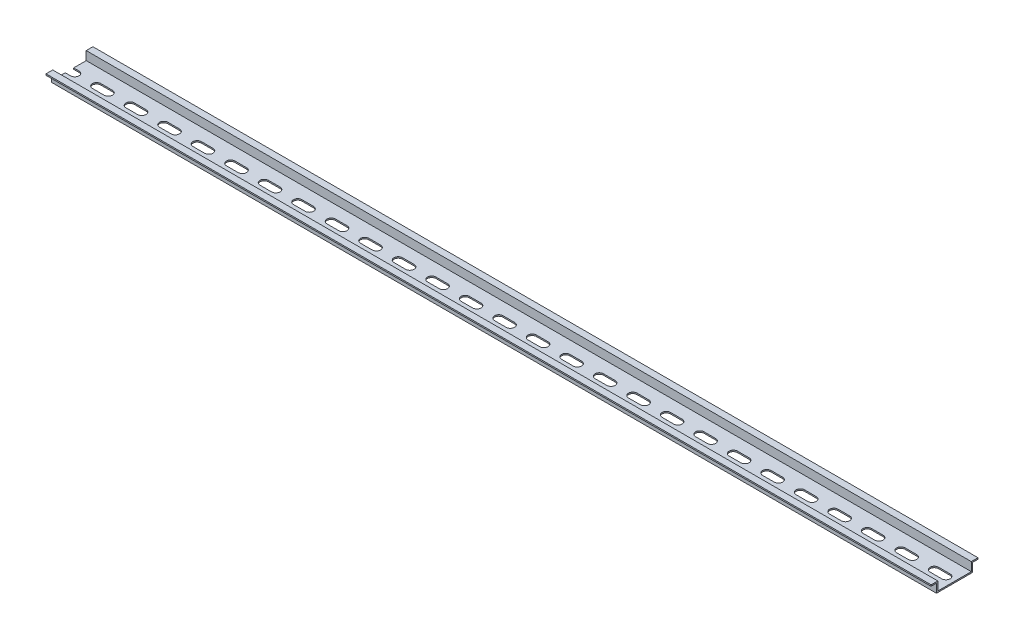
SolidWorks part; units mm, degrees
material "Plain Carbon Steel"
ref_plane "Front Plane" through (0, 0, 0) normal (0, 0, 1) x (1, 0, 0)
ref_plane "Top Plane" through (0, 0, 0) normal (0, 1, 0) x (1, 0, 0)
ref_plane "Right Plane" through (0, 0, 0) normal (1, 0, 0) x (0, 0, -1)
sketch "Sketch1" plane through (0, 0, 0) normal (0, 0, 1) x (1, 0, 0)
  line L1 (-500, 0) -> (500, 0)
  line L2 (-500, 0) -> (-500, 7.5)
  line L3 (-500, 7.5) -> (500, 7.5)
  line L4 (500, 0) -> (500, 7.5)
  point P0 (0, 0)
  point P7 (0, 0)
  dimension "D1" = 1000
  dimension "D2" = 7.5
extrude "Boss-Extrude1" add sketch "Sketch1" along normal mid plane 35
sketch "Sketch2" plane through (0, 7.5, 0) normal (0, 1, 0) x (1, 0, 0)
  line L0 (-500, -17.5) -> (-500, 17.5) construction
  line L1 (-500, -12.5) -> (500, -12.5)
  line L2 (-500, -12.5) -> (-500, 12.5)
  line L3 (-500, 12.5) -> (500, 12.5)
  line L4 (500, -12.5) -> (500, 12.5)
  line L5 (500, -17.5) -> (500, 17.5) construction
  line L6 (-500, 0) -> (500, 0) construction
  point P10 (0, 0)
  dimension "D1" = 25
extrude "Cut-Extrude1" cut sketch "Sketch2" against normal offset from surface (6.5 mm away) 1 up to face at (0, 0, 0)
sketch "Sketch4" plane through (500, 0, 0) normal (1, 0, 0) x (0, 0, -1)
  line L0 (0, 0) -> (0, 6.5) construction
  line L1 (-17.5, 0) -> (-13.5, 0)
  line L2 (-17.5, 0) -> (-17.5, 6.5)
  line L4 (-13.5, 0) -> (-13.5, 6.5)
  line L5 (17.5, 0) -> (13.5, 0)
  line L6 (17.5, 0) -> (17.5, 6.5)
  line L7 (17.5, 6.5) -> (13.5, 6.5)
  line L8 (13.5, 0) -> (13.5, 6.5)
  line L9 (-17.5, 0) -> (17.5, 0) construction
  line L11 (-17.5, 6.5) -> (-13.5, 6.5)
  line L12 (-17.5, 7.5) -> (-12.5, 7.5) construction
  line L13 (-12.5, 1) -> (-12.5, 7.5) construction
  dimension "D1" = 1
  dimension "D2" = 1
extrude "Cut-Extrude2" cut sketch "Sketch4" against normal through all both and the other way through all
sketch "Sketch5" plane through (0, 1, 0) normal (0, 1, 0) x (1, 0, 0)
  line L0 (-504.69, 0) -> (-496.01, 0) construction
  line L1 (-504.69, 3.16) -> (-496.01, 3.16)
  line L2 (-504.69, -3.16) -> (-496.01, -3.16)
  line L3 (-500, -12.5) -> (-500, 12.5) construction
  line L4 (-504.69, 0) -> (-479.69, 0) construction
  line L5 (-492.85, 0) -> (-482.85, 0) construction
  line L6 (-479.69, 0) -> (-471.01, 0) construction
  line L7 (-479.69, 3.16) -> (-471.01, 3.16)
  line L8 (-479.69, -3.16) -> (-471.01, -3.16)
  line L9 (-454.69, 0) -> (-446.01, 0) construction
  line L10 (-454.69, 3.16) -> (-446.01, 3.16)
  line L11 (-454.69, -3.16) -> (-446.01, -3.16)
  line L12 (-429.69, 0) -> (-421.01, 0) construction
  line L13 (-429.69, 3.16) -> (-421.01, 3.16)
  line L14 (-429.69, -3.16) -> (-421.01, -3.16)
  line L15 (-404.69, 0) -> (-396.01, 0) construction
  line L16 (-404.69, 3.16) -> (-396.01, 3.16)
  line L17 (-404.69, -3.16) -> (-396.01, -3.16)
  line L18 (-379.69, 0) -> (-371.01, 0) construction
  line L19 (-379.69, 3.16) -> (-371.01, 3.16)
  line L20 (-379.69, -3.16) -> (-371.01, -3.16)
  line L21 (-354.69, 0) -> (-346.01, 0) construction
  line L22 (-354.69, 3.16) -> (-346.01, 3.16)
  line L23 (-354.69, -3.16) -> (-346.01, -3.16)
  line L24 (-329.69, 0) -> (-321.01, 0) construction
  line L25 (-329.69, 3.16) -> (-321.01, 3.16)
  line L26 (-329.69, -3.16) -> (-321.01, -3.16)
  line L27 (-304.69, 0) -> (-296.01, 0) construction
  line L28 (-304.69, 3.16) -> (-296.01, 3.16)
  line L29 (-304.69, -3.16) -> (-296.01, -3.16)
  line L30 (-279.69, 0) -> (-271.01, 0) construction
  line L31 (-279.69, 3.16) -> (-271.01, 3.16)
  line L32 (-279.69, -3.16) -> (-271.01, -3.16)
  line L33 (-254.69, 0) -> (-246.01, 0) construction
  line L34 (-254.69, 3.16) -> (-246.01, 3.16)
  line L35 (-254.69, -3.16) -> (-246.01, -3.16)
  line L36 (-229.69, 0) -> (-221.01, 0) construction
  line L37 (-229.69, 3.16) -> (-221.01, 3.16)
  line L38 (-229.69, -3.16) -> (-221.01, -3.16)
  line L39 (-204.69, 0) -> (-196.01, 0) construction
  line L40 (-204.69, 3.16) -> (-196.01, 3.16)
  line L41 (-204.69, -3.16) -> (-196.01, -3.16)
  line L42 (-179.69, 0) -> (-171.01, 0) construction
  line L43 (-179.69, 3.16) -> (-171.01, 3.16)
  line L44 (-179.69, -3.16) -> (-171.01, -3.16)
  line L45 (-154.69, 0) -> (-146.01, 0) construction
  line L46 (-154.69, 3.16) -> (-146.01, 3.16)
  line L47 (-154.69, -3.16) -> (-146.01, -3.16)
  line L48 (-129.69, 0) -> (-121.01, 0) construction
  line L49 (-129.69, 3.16) -> (-121.01, 3.16)
  line L50 (-129.69, -3.16) -> (-121.01, -3.16)
  line L51 (-104.69, 0) -> (-96.01, 0) construction
  line L52 (-104.69, 3.16) -> (-96.01, 3.16)
  line L53 (-104.69, -3.16) -> (-96.01, -3.16)
  line L54 (-79.69, 0) -> (-71.01, 0) construction
  line L55 (-79.69, 3.16) -> (-71.01, 3.16)
  line L56 (-79.69, -3.16) -> (-71.01, -3.16)
  line L57 (-54.69, 0) -> (-46.01, 0) construction
  line L58 (-54.69, 3.16) -> (-46.01, 3.16)
  line L59 (-54.69, -3.16) -> (-46.01, -3.16)
  line L60 (-29.69, 0) -> (-21.01, 0) construction
  line L61 (-29.69, 3.16) -> (-21.01, 3.16)
  line L62 (-29.69, -3.16) -> (-21.01, -3.16)
  line L63 (-4.69, 0) -> (3.99, 0) construction
  line L64 (-4.69, 3.16) -> (3.99, 3.16)
  line L65 (-4.69, -3.16) -> (3.99, -3.16)
  line L66 (20.31, 0) -> (28.99, 0) construction
  line L67 (20.31, 3.16) -> (28.99, 3.16)
  line L68 (20.31, -3.16) -> (28.99, -3.16)
  line L69 (45.31, 0) -> (53.99, 0) construction
  line L70 (45.31, 3.16) -> (53.99, 3.16)
  line L71 (45.31, -3.16) -> (53.99, -3.16)
  line L72 (70.31, 0) -> (78.99, 0) construction
  line L73 (70.31, 3.16) -> (78.99, 3.16)
  line L74 (70.31, -3.16) -> (78.99, -3.16)
  line L75 (95.31, 0) -> (103.99, 0) construction
  line L76 (95.31, 3.16) -> (103.99, 3.16)
  line L77 (95.31, -3.16) -> (103.99, -3.16)
  line L78 (120.31, 0) -> (128.99, 0) construction
  line L79 (120.31, 3.16) -> (128.99, 3.16)
  line L80 (120.31, -3.16) -> (128.99, -3.16)
  line L81 (145.31, 0) -> (153.99, 0) construction
  line L82 (145.31, 3.16) -> (153.99, 3.16)
  line L83 (145.31, -3.16) -> (153.99, -3.16)
  line L84 (170.31, 0) -> (178.99, 0) construction
  line L85 (170.31, 3.16) -> (178.99, 3.16)
  line L86 (170.31, -3.16) -> (178.99, -3.16)
  line L87 (195.31, 0) -> (203.99, 0) construction
  line L88 (195.31, 3.16) -> (203.99, 3.16)
  line L89 (195.31, -3.16) -> (203.99, -3.16)
  line L90 (220.31, 0) -> (228.99, 0) construction
  line L91 (220.31, 3.16) -> (228.99, 3.16)
  line L92 (220.31, -3.16) -> (228.99, -3.16)
  line L93 (245.31, 0) -> (253.99, 0) construction
  line L94 (245.31, 3.16) -> (253.99, 3.16)
  line L95 (245.31, -3.16) -> (253.99, -3.16)
  line L96 (270.31, 0) -> (278.99, 0) construction
  line L97 (270.31, 3.16) -> (278.99, 3.16)
  line L98 (270.31, -3.16) -> (278.99, -3.16)
  line L99 (295.31, 0) -> (303.99, 0) construction
  line L100 (295.31, 3.16) -> (303.99, 3.16)
  line L101 (295.31, -3.16) -> (303.99, -3.16)
  line L102 (320.31, 0) -> (328.99, 0) construction
  line L103 (320.31, 3.16) -> (328.99, 3.16)
  line L104 (320.31, -3.16) -> (328.99, -3.16)
  line L105 (345.31, 0) -> (353.99, 0) construction
  line L106 (345.31, 3.16) -> (353.99, 3.16)
  line L107 (345.31, -3.16) -> (353.99, -3.16)
  line L108 (370.31, 0) -> (378.99, 0) construction
  line L109 (370.31, 3.16) -> (378.99, 3.16)
  line L110 (370.31, -3.16) -> (378.99, -3.16)
  line L111 (395.31, 0) -> (403.99, 0) construction
  line L112 (395.31, 3.16) -> (403.99, 3.16)
  line L113 (395.31, -3.16) -> (403.99, -3.16)
  line L114 (420.31, 0) -> (428.99, 0) construction
  line L115 (420.31, 3.16) -> (428.99, 3.16)
  line L116 (420.31, -3.16) -> (428.99, -3.16)
  line L117 (445.31, 0) -> (453.99, 0) construction
  line L118 (445.31, 3.16) -> (453.99, 3.16)
  line L119 (445.31, -3.16) -> (453.99, -3.16)
  line L120 (470.31, 0) -> (478.99, 0) construction
  line L121 (470.31, 3.16) -> (478.99, 3.16)
  line L122 (470.31, -3.16) -> (478.99, -3.16)
  line L123 (495.31, 0) -> (503.99, 0) construction
  line L124 (495.31, 3.16) -> (503.99, 3.16)
  line L125 (495.31, -3.16) -> (503.99, -3.16)
  arc A0 (-504.69, 3.16) -> (-504.69, -3.16) centre (-504.69, 0) ccw
  arc A1 (-496.01, -3.16) -> (-496.01, 3.16) centre (-496.01, 0) ccw
  arc A2 (-479.69, 3.16) -> (-479.69, -3.16) centre (-479.69, 0) ccw
  arc A3 (-471.01, -3.16) -> (-471.01, 3.16) centre (-471.01, 0) ccw
  arc A4 (-454.69, 3.16) -> (-454.69, -3.16) centre (-454.69, 0) ccw
  arc A5 (-446.01, -3.16) -> (-446.01, 3.16) centre (-446.01, 0) ccw
  arc A6 (-429.69, 3.16) -> (-429.69, -3.16) centre (-429.69, 0) ccw
  arc A7 (-421.01, -3.16) -> (-421.01, 3.16) centre (-421.01, 0) ccw
  arc A8 (-404.69, 3.16) -> (-404.69, -3.16) centre (-404.69, 0) ccw
  arc A9 (-396.01, -3.16) -> (-396.01, 3.16) centre (-396.01, 0) ccw
  arc A10 (-379.69, 3.16) -> (-379.69, -3.16) centre (-379.69, 0) ccw
  arc A11 (-371.01, -3.16) -> (-371.01, 3.16) centre (-371.01, 0) ccw
  arc A12 (-354.69, 3.16) -> (-354.69, -3.16) centre (-354.69, 0) ccw
  arc A13 (-346.01, -3.16) -> (-346.01, 3.16) centre (-346.01, 0) ccw
  arc A14 (-329.69, 3.16) -> (-329.69, -3.16) centre (-329.69, 0) ccw
  arc A15 (-321.01, -3.16) -> (-321.01, 3.16) centre (-321.01, 0) ccw
  arc A16 (-304.69, 3.16) -> (-304.69, -3.16) centre (-304.69, 0) ccw
  arc A17 (-296.01, -3.16) -> (-296.01, 3.16) centre (-296.01, 0) ccw
  arc A18 (-279.69, 3.16) -> (-279.69, -3.16) centre (-279.69, 0) ccw
  arc A19 (-271.01, -3.16) -> (-271.01, 3.16) centre (-271.01, 0) ccw
  arc A20 (-254.69, 3.16) -> (-254.69, -3.16) centre (-254.69, 0) ccw
  arc A21 (-246.01, -3.16) -> (-246.01, 3.16) centre (-246.01, 0) ccw
  arc A22 (-229.69, 3.16) -> (-229.69, -3.16) centre (-229.69, 0) ccw
  arc A23 (-221.01, -3.16) -> (-221.01, 3.16) centre (-221.01, 0) ccw
  arc A24 (-204.69, 3.16) -> (-204.69, -3.16) centre (-204.69, 0) ccw
  arc A25 (-196.01, -3.16) -> (-196.01, 3.16) centre (-196.01, 0) ccw
  arc A26 (-179.69, 3.16) -> (-179.69, -3.16) centre (-179.69, 0) ccw
  arc A27 (-171.01, -3.16) -> (-171.01, 3.16) centre (-171.01, 0) ccw
  arc A28 (-154.69, 3.16) -> (-154.69, -3.16) centre (-154.69, 0) ccw
  arc A29 (-146.01, -3.16) -> (-146.01, 3.16) centre (-146.01, 0) ccw
  arc A30 (-129.69, 3.16) -> (-129.69, -3.16) centre (-129.69, 0) ccw
  arc A31 (-121.01, -3.16) -> (-121.01, 3.16) centre (-121.01, 0) ccw
  arc A32 (-104.69, 3.16) -> (-104.69, -3.16) centre (-104.69, 0) ccw
  arc A33 (-96.01, -3.16) -> (-96.01, 3.16) centre (-96.01, 0) ccw
  arc A34 (-79.69, 3.16) -> (-79.69, -3.16) centre (-79.69, 0) ccw
  arc A35 (-71.01, -3.16) -> (-71.01, 3.16) centre (-71.01, 0) ccw
  arc A36 (-54.69, 3.16) -> (-54.69, -3.16) centre (-54.69, 0) ccw
  arc A37 (-46.01, -3.16) -> (-46.01, 3.16) centre (-46.01, 0) ccw
  arc A38 (-29.69, 3.16) -> (-29.69, -3.16) centre (-29.69, 0) ccw
  arc A39 (-21.01, -3.16) -> (-21.01, 3.16) centre (-21.01, 0) ccw
  arc A40 (-4.69, 3.16) -> (-4.69, -3.16) centre (-4.69, 0) ccw
  arc A41 (3.99, -3.16) -> (3.99, 3.16) centre (3.99, 0) ccw
  arc A42 (20.31, 3.16) -> (20.31, -3.16) centre (20.31, 0) ccw
  arc A43 (28.99, -3.16) -> (28.99, 3.16) centre (28.99, 0) ccw
  arc A44 (45.31, 3.16) -> (45.31, -3.16) centre (45.31, 0) ccw
  arc A45 (53.99, -3.16) -> (53.99, 3.16) centre (53.99, 0) ccw
  arc A46 (70.31, 3.16) -> (70.31, -3.16) centre (70.31, 0) ccw
  arc A47 (78.99, -3.16) -> (78.99, 3.16) centre (78.99, 0) ccw
  arc A48 (95.31, 3.16) -> (95.31, -3.16) centre (95.31, 0) ccw
  arc A49 (103.99, -3.16) -> (103.99, 3.16) centre (103.99, 0) ccw
  arc A50 (120.31, 3.16) -> (120.31, -3.16) centre (120.31, 0) ccw
  arc A51 (128.99, -3.16) -> (128.99, 3.16) centre (128.99, 0) ccw
  arc A52 (145.31, 3.16) -> (145.31, -3.16) centre (145.31, 0) ccw
  arc A53 (153.99, -3.16) -> (153.99, 3.16) centre (153.99, 0) ccw
  arc A54 (170.31, 3.16) -> (170.31, -3.16) centre (170.31, 0) ccw
  arc A55 (178.99, -3.16) -> (178.99, 3.16) centre (178.99, 0) ccw
  arc A56 (195.31, 3.16) -> (195.31, -3.16) centre (195.31, 0) ccw
  arc A57 (203.99, -3.16) -> (203.99, 3.16) centre (203.99, 0) ccw
  arc A58 (220.31, 3.16) -> (220.31, -3.16) centre (220.31, 0) ccw
  arc A59 (228.99, -3.16) -> (228.99, 3.16) centre (228.99, 0) ccw
  arc A60 (245.31, 3.16) -> (245.31, -3.16) centre (245.31, 0) ccw
  arc A61 (253.99, -3.16) -> (253.99, 3.16) centre (253.99, 0) ccw
  arc A62 (270.31, 3.16) -> (270.31, -3.16) centre (270.31, 0) ccw
  arc A63 (278.99, -3.16) -> (278.99, 3.16) centre (278.99, 0) ccw
  arc A64 (295.31, 3.16) -> (295.31, -3.16) centre (295.31, 0) ccw
  arc A65 (303.99, -3.16) -> (303.99, 3.16) centre (303.99, 0) ccw
  arc A66 (320.31, 3.16) -> (320.31, -3.16) centre (320.31, 0) ccw
  arc A67 (328.99, -3.16) -> (328.99, 3.16) centre (328.99, 0) ccw
  arc A68 (345.31, 3.16) -> (345.31, -3.16) centre (345.31, 0) ccw
  arc A69 (353.99, -3.16) -> (353.99, 3.16) centre (353.99, 0) ccw
  arc A70 (370.31, 3.16) -> (370.31, -3.16) centre (370.31, 0) ccw
  arc A71 (378.99, -3.16) -> (378.99, 3.16) centre (378.99, 0) ccw
  arc A72 (395.31, 3.16) -> (395.31, -3.16) centre (395.31, 0) ccw
  arc A73 (403.99, -3.16) -> (403.99, 3.16) centre (403.99, 0) ccw
  arc A74 (420.31, 3.16) -> (420.31, -3.16) centre (420.31, 0) ccw
  arc A75 (428.99, -3.16) -> (428.99, 3.16) centre (428.99, 0) ccw
  arc A76 (445.31, 3.16) -> (445.31, -3.16) centre (445.31, 0) ccw
  arc A77 (453.99, -3.16) -> (453.99, 3.16) centre (453.99, 0) ccw
  arc A78 (470.31, 3.16) -> (470.31, -3.16) centre (470.31, 0) ccw
  arc A79 (478.99, -3.16) -> (478.99, 3.16) centre (478.99, 0) ccw
  arc A80 (495.31, 3.16) -> (495.31, -3.16) centre (495.31, 0) ccw
  arc A81 (503.99, -3.16) -> (503.99, 3.16) centre (503.99, 0) ccw
  point P3 (-500.35, 0)
  point P11 (-507.85, 0)
  point P14 (-492.85, 0)
  point P17 (-475.35, 0)
  point P24 (-450.35, 0)
  point P31 (-425.35, 0)
  point P38 (-400.35, 0)
  point P45 (-375.35, 0)
  point P52 (-350.35, 0)
  point P59 (-325.35, 0)
  point P66 (-300.35, 0)
  point P73 (-275.35, 0)
  point P80 (-250.35, 0)
  point P87 (-225.35, 0)
  point P94 (-200.35, 0)
  point P101 (-175.35, 0)
  point P108 (-150.35, 0)
  point P115 (-125.35, 0)
  point P122 (-100.35, 0)
  point P129 (-75.35, 0)
  point P136 (-50.35, 0)
  point P143 (-25.35, 0)
  point P150 (-0.35, 0)
  point P157 (24.65, 0)
  point P164 (49.65, 0)
  point P171 (74.65, 0)
  point P178 (99.65, 0)
  point P185 (124.65, 0)
  point P192 (149.65, 0)
  point P199 (174.65, 0)
  point P206 (199.65, 0)
  point P213 (224.65, 0)
  point P220 (249.65, 0)
  point P227 (274.65, 0)
  point P234 (299.65, 0)
  point P241 (324.65, 0)
  point P248 (349.65, 0)
  point P255 (374.65, 0)
  point P262 (399.65, 0)
  point P269 (424.65, 0)
  point P276 (449.65, 0)
  point P283 (474.65, 0)
  point P290 (499.65, 0)
  dimension "D1" = 7.15
  dimension "D2" = 6.32
  dimension "D3" = 15
  dimension "D4" = 10
  dimension "D6" = 25
  dimension "D5" = 41
extrude "Cut-Extrude3" cut sketch "Sketch5" against normal through all
sketch "Sketch6" plane through (500, 0, 0) normal (1, 0, 0) x (0, 0, -1)
  line L0 (3.16, 0) -> (13.5, 0) construction
  line L1 (-17.5, 7.5) -> (17.5, 7.5)
  line L2 (-17.5, 7.5) -> (-17.5, 0)
  line L3 (-17.5, 0) -> (17.5, 0)
  line L4 (17.5, 7.5) -> (17.5, 0)
  point P5 (17.5, 7.5)
  point P7 (17.5, -3.3424)
extrude "Cut-Extrude4" cut sketch "Sketch6" against normal offset from surface (339.6 mm away) 660.4 up to face at (-500, 3.75, 11.665)
